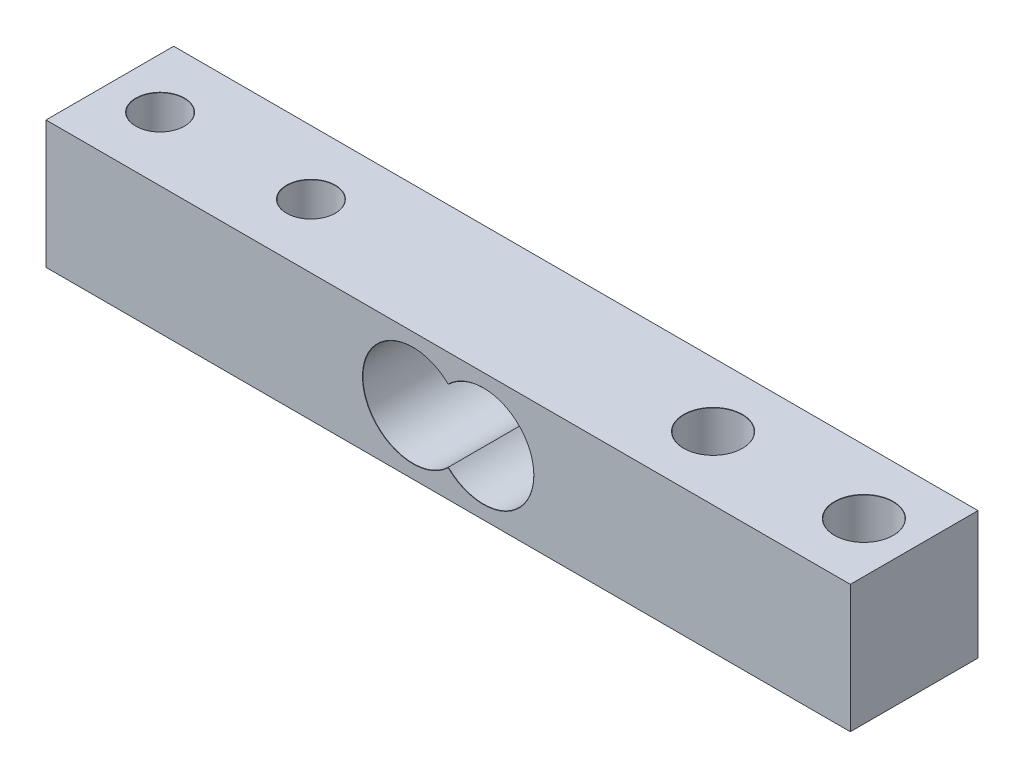
SolidWorks part; units mm, degrees
ref_plane "Front Plane" through (0, 0, 0) normal (0, 0, 1) x (1, 0, 0)
ref_plane "Top Plane" through (0, 0, 0) normal (0, 1, 0) x (1, 0, 0)
ref_plane "Right Plane" through (0, 0, 0) normal (1, 0, 0) x (0, 0, -1)
sketch "Sketch1" plane through (0, 0, 0) normal (0, 1, 0) x (1, 0, 0)
  line L1 (-40, -6.35) -> (40, -6.35)
  line L2 (-40, -6.35) -> (-40, 6.35)
  line L3 (-40, 6.35) -> (40, 6.35)
  line L4 (40, -6.35) -> (40, 6.35)
  line L5 (-40, -6.35) -> (40, 6.35) construction
  line L6 (-40, 6.35) -> (40, -6.35) construction
  point P0 (0, 0)
  dimension "D1" = 12.7
  dimension "D2" = 80
extrude "Boss-Extrude1" add sketch "Sketch1" along normal blind 12.7
hole_wizard "M4 Clearance Hole1" positions "Sketch2" profile "Sketch3" hole size "M4" standard "ANSI Metric" end condition through all
sketch "Sketch2" plane through (0, 12.7, 0) normal (0, 1, 0) x (1, 0, 0)
  line L0 (-35, 0) -> (-20, 0) construction
  line L1 (20, 0) -> (35, 0) construction
  line L3 (-20, 0) -> (20, 0) construction
  point P0 (-35, 0)
  point P2 (-20, 0)
  point P15 (0, 0)
  point P16 (0, 0)
  dimension "D1" = 15
  dimension "D2" = 40
sketch "Sketch3" plane through (-35, 12.7, 0) normal (1, 0, 0) x (0, 0, 1)
  line L0 (0, 0) -> (0, 12.7)
  line L1 (0, 12.7) -> (2.4, 12.7)
  line L2 (2.4, 12.7) -> (2.4, 0.021)
  line L3 (2.4, 0.021) -> (2.425, 0)
  line L5 (2.425, 0) -> (0, 0)
  line L6 (-2.4, 0.021) -> (-2.425, 0) construction
  line L11 (0, -6.35) -> (0, 107.95) construction
  dimension "Thru Hole Dia." = 4.8
  dimension "Thru Hole Depth" = 12.7
  dimension "Near C'Sink Dia." = 4.85
  dimension "Near C'Sink Angle" = 100
hole_wizard "M8 Clearance Hole1" positions "Sketch4" profile "Sketch5" hole size "M8" standard "ANSI Metric" end condition through all
sketch "Sketch4" plane through (0, 0, 6.35) normal (0, 0, 1) x (1, 0, 0)
  line L0 (-3.5, 6.35) -> (3.5, 6.35) construction
  line L2 (-40, 12.7) -> (-40, 0) construction
  point P0 (-3.5, 6.35)
  point P2 (3.5, 6.35)
  point P9 (0, 6.35)
  point P13 (-40, 6.35)
  dimension "D1" = 7
sketch "Sketch5" plane through (-3.5, 6.35, 6.35) normal (1, 0, 0) x (0, -1, 0)
  line L0 (0, 0) -> (0, 12.7)
  line L1 (0, 12.7) -> (5, 12.7)
  line L2 (5, 12.7) -> (5, 0.021)
  line L3 (5, 0.021) -> (5.025, 0)
  line L5 (5.025, 0) -> (0, 0)
  line L6 (-5, 0.021) -> (-5.025, 0) construction
  line L11 (0, -6.35) -> (0, 107.95) construction
  dimension "Thru Hole Dia." = 10
  dimension "Thru Hole Depth" = 12.7
  dimension "Near C'Sink Dia." = 10.05
  dimension "Near C'Sink Angle" = 100
hole_wizard "M5 Clearance Hole1" positions "Sketch6" profile "Sketch7" hole size "M5" standard "ANSI Metric" end condition through all
sketch "Sketch6" plane through (0, 12.7, 0) normal (0, 1, 0) x (1, 0, 0)
  line L0 (35, 0) -> (20, 0) construction
  line L1 (20, 0) -> (-20, 0) construction
  point P0 (35, 0)
  point P2 (20, 0)
  point P12 (0, 0)
  dimension "D1" = 15
sketch "Sketch7" plane through (35, 12.7, 0) normal (1, 0, 0) x (0, 0, 1)
  line L0 (0, 0) -> (0, 12.7)
  line L1 (0, 12.7) -> (2.9, 12.7)
  line L2 (2.9, 12.7) -> (2.9, 0.021)
  line L3 (2.9, 0.021) -> (2.925, 0)
  line L5 (2.925, 0) -> (0, 0)
  line L6 (-2.9, 0.021) -> (-2.925, 0) construction
  line L11 (0, -6.35) -> (0, 107.95) construction
  dimension "Thru Hole Dia." = 5.8
  dimension "Thru Hole Depth" = 12.7
  dimension "Near C'Sink Dia." = 5.85
  dimension "Near C'Sink Angle" = 100
